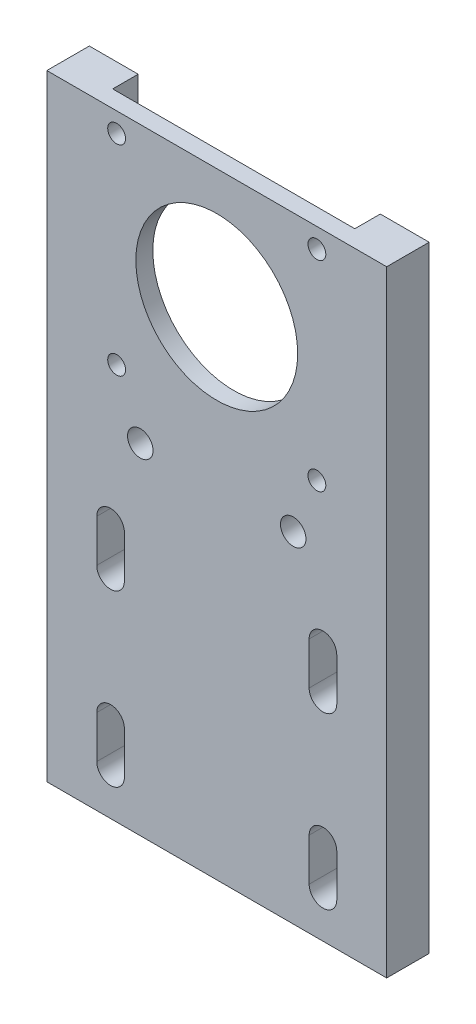
SolidWorks part; units mm, degrees
material "Д16Т ГОСТ 4784-74"
ref_plane "Спереди" through (0, 0, 0) normal (0, 0, 1) x (1, 0, 0)
ref_plane "Сверху" through (0, 0, 0) normal (0, 1, 0) x (1, 0, 0)
ref_plane "Справа" through (0, 0, 0) normal (1, 0, 0) x (0, 0, -1)
sketch "Эскиз1" plane through (0, 0, 0) normal (0, 0, 1) x (1, 0, 0)
  line L0 (40, 145) -> (40, 0) construction
  line L1 (0, 0) -> (80, 0)
  line L2 (0, 0) -> (0, 145)
  line L3 (0, 145) -> (80, 145)
  line L4 (80, 0) -> (80, 145)
  line L5 (15, 60) -> (15, 50) construction
  line L6 (18.25, 60) -> (18.25, 50)
  line L7 (11.75, 60) -> (11.75, 50)
  line L8 (15, 20) -> (15, 10) construction
  line L9 (18.25, 20) -> (18.25, 10)
  line L10 (11.75, 20) -> (11.75, 10)
  line L11 (65, 20) -> (65, 10) construction
  line L12 (61.75, 20) -> (61.75, 10)
  line L13 (68.25, 20) -> (68.25, 10)
  line L14 (65, 60) -> (65, 50) construction
  line L15 (61.75, 60) -> (61.75, 50)
  line L16 (68.25, 60) -> (68.25, 50)
  circle A0 centre (40, 116.8) radius 19.05
  arc A1 (18.25, 60) -> (11.75, 60) centre (15, 60) ccw
  arc A2 (11.75, 50) -> (18.25, 50) centre (15, 50) ccw
  arc A3 (18.25, 20) -> (11.75, 20) centre (15, 20) ccw
  arc A4 (11.75, 10) -> (18.25, 10) centre (15, 10) ccw
  arc A5 (61.75, 20) -> (68.25, 20) centre (65, 20) cw
  arc A6 (68.25, 10) -> (61.75, 10) centre (65, 10) cw
  arc A7 (61.75, 60) -> (68.25, 60) centre (65, 60) cw
  arc A8 (68.25, 50) -> (61.75, 50) centre (65, 50) cw
  point P11 (15, 55)
  point P20 (15, 15)
  point P25 (65, 15)
  point P32 (65, 55)
  dimension "D3" = 38.1
  dimension "D4" = 28.2
  dimension "D5" = 3.25
  dimension "D1" = 80
  dimension "D2" = 145
  dimension "D6" = 10
  dimension "D7" = 55
  dimension "D8" = 25
  dimension "D10" = 40
  dimension "D9" = 2
extrude "Бобышка-Вытянуть1" add sketch "Эскиз1" along normal blind 10
sketch "Эскиз4" plane through (0, 0, 0) normal (0, 0, -1) x (-1, 0, 0)
  line L0 (-80, 145) -> (0, 145) construction
  line L1 (-68.5, 145) -> (-11.5, 145)
  line L2 (-68.5, 145) -> (-68.5, 90.5)
  line L3 (-66, 88) -> (-14, 88)
  line L4 (-11.5, 145) -> (-11.5, 90.5)
  line L5 (-40, 116.8) -> (-40, 145) construction
  arc A0 (-11.5, 90.5) -> (-14, 88) centre (-14, 90.5) cw
  arc A1 (-68.5, 90.5) -> (-66, 88) centre (-66, 90.5) ccw
  point P11 (-11.5, 88)
  point P14 (-68.5, 88)
  dimension "D3" = 2.5
  dimension "D1" = 57
  dimension "D2" = 57
extrude "Вырез-Вытянуть1" cut sketch "Эскиз4" against normal blind 6
hole_wizard "Отверстие обработанное метчиком M51" positions "Эскиз3" profile "Эскиз2" tap size "M5" standard "DIN"
sketch "Эскиз3" plane through (24.3447, -10.7131, 6) normal (0, 0, -1) x (-1, 0, 0)
  line L1 (-39.2253, 151.0831) -> (7.9147, 151.0831)
  line L2 (-39.2253, 151.0831) -> (-39.2253, 103.9431)
  line L3 (-39.2253, 103.9431) -> (7.9147, 103.9431)
  line L4 (7.9147, 151.0831) -> (7.9147, 103.9431)
  circle A0 centre (-15.6553, 127.5131) radius 33.333
  point P0 (7.9147, 103.9431)
  point P1 (7.9147, 151.0831)
  point P3 (-39.2253, 151.0831)
  point P5 (-39.2253, 103.9431)
  dimension "D1" = 47.14
sketch "Эскиз2" plane through (16.43, 93.23, 6) normal (1, 0, 0) x (0, 1, 0)
  line L0 (0, 0) -> (0, 15.2618)
  line L1 (0, 15.2618) -> (2.1, 14)
  line L2 (2.1, 14) -> (2.1, 0.2454)
  line L3 (2.1, 0.2454) -> (2.525, 0)
  line L5 (2.525, 0) -> (0, 0)
  line L6 (-2.1, 0.2454) -> (-2.525, 0) construction
  line L10 (0, 15.2618) -> (-2.1, 14) construction
  line L11 (0, -6.35) -> (0, 107.95) construction
  dimension "Диаметр сверла" = 4.2
  dimension "Глубина сверла" = 14
  dimension "Диаметр передней зенковки" = 5.05
  dimension "Угол передней зенковки" = 120
  dimension "Угол заточки сверла" = 118
cosmetic thread "Отверстие резьбы1" parameters "D1"=5, "D2"=5
cosmetic thread "Отверстие резьбы2" parameters "D1"=5, "D2"=5
cosmetic thread "Отверстие резьбы3" parameters "D1"=5, "D2"=5
cosmetic thread "Отверстие резьбы4" parameters "D1"=5, "D2"=5
sketch "Эскиз5" plane through (0, 0, 10) normal (0, 0, 1) x (1, 0, 0)
  line L0 (40, 0) -> (40, 145) construction
  line L1 (0, 0) -> (80, 0) construction
  line L2 (80, 145) -> (0, 145) construction
  line L3 (22, 80) -> (58, 80) construction
  circle A0 centre (22, 80) radius 3
  circle A1 centre (58, 80) radius 3
  dimension "D2" = 6
  dimension "D1" = 80
  dimension "D3" = 36
extrude "Вырез-Вытянуть2" cut sketch "Эскиз5" against normal blind 7
hole_wizard "Зенковка для винта с потайной головкой и внутренним шестигранником M41" positions "Эскиз7" profile "Эскиз6" countersink size "M4" standard "DIN" end condition through all
sketch "Эскиз7" plane through (0, 0, 0) normal (0, 0, -1) x (-1, 0, 0)
  circle A0 centre (-58, 80) radius 3 construction
  circle A1 centre (-22, 80) radius 3 construction
  point P0 (-22, 80)
  point P1 (-58, 80)
sketch "Эскиз6" plane through (22, 80, 0) normal (1, 0, 0) x (0, 1, 0)
  line L0 (0, 0) -> (0, 10)
  line L1 (0, 10) -> (2.25, 10)
  line L2 (2.25, 10) -> (2.25, 2.34)
  line L3 (2.25, 2.34) -> (4.59, 0)
  line L5 (4.59, 0) -> (0, 0)
  line L6 (-2.25, 2.34) -> (-4.59, 0) construction
  line L11 (0, -6.35) -> (0, 107.95) construction
  dimension "Диаметр сквозного отверстия" = 4.5
  dimension "Глубина сквозного отверстия" = 10
  dimension "Диаметр передней зенковки" = 9.18
  dimension "Угол передней зенковки" = 90
